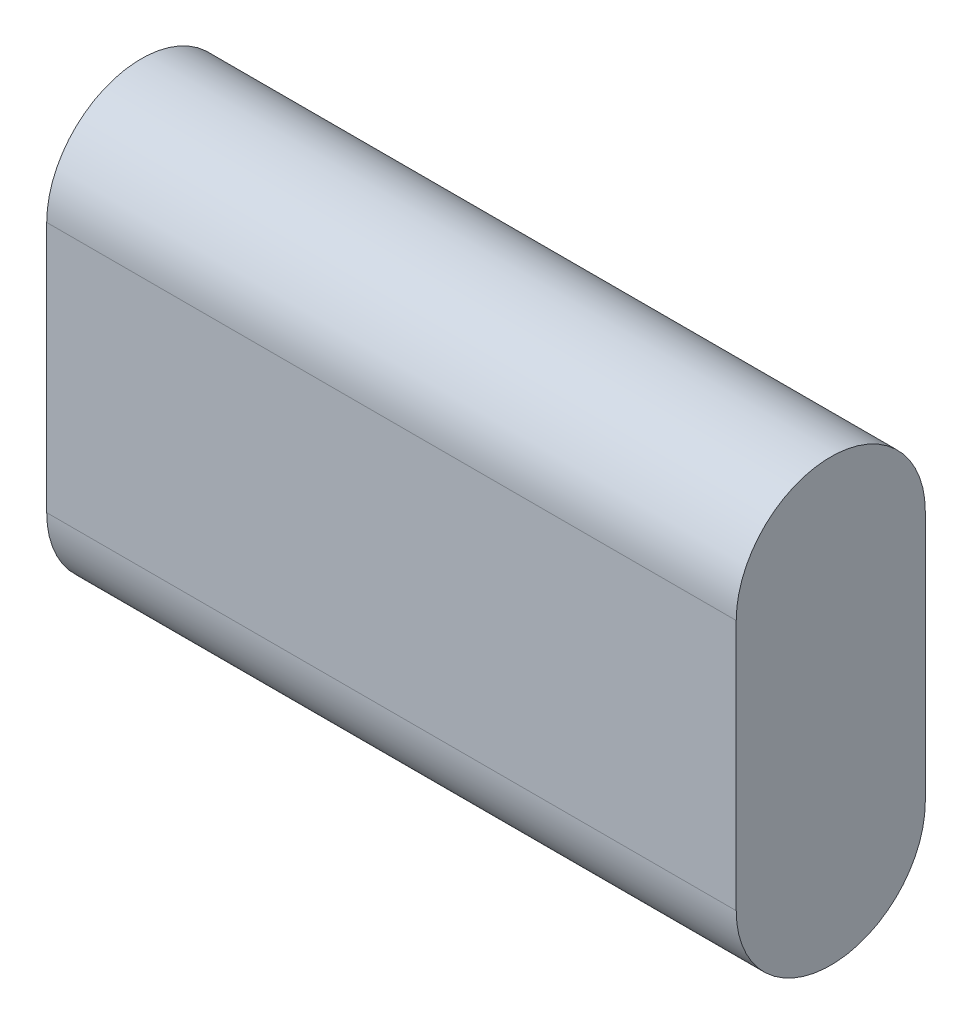
SolidWorks part; units mm, degrees
ref_plane "正面" through (0, 0, 0) normal (0, 0, 1) x (1, 0, 0)
ref_plane "平面" through (0, 0, 0) normal (0, 1, 0) x (1, 0, 0)
ref_plane "右側面" through (0, 0, 0) normal (1, 0, 0) x (0, 0, -1)
sketch "ｽｹｯﾁ1" plane through (0, 0, 0) normal (1, 0, 0) x (0, 0, -1)
  line L0 (0, -5.65) -> (0, 5.65) construction
  line L1 (-4.25, -5.65) -> (-4.25, 5.65)
  line L2 (4.25, -5.65) -> (4.25, 5.65)
  arc A0 (-4.25, -5.65) -> (4.25, -5.65) centre (0, -5.65) ccw
  arc A1 (4.25, 5.65) -> (-4.25, 5.65) centre (0, 5.65) ccw
  point P2 (0, 0)
  dimension "D2" = 19.8
  dimension "D1" = 8.5
extrude "ﾎﾞｽ - 押し出し1" add sketch "ｽｹｯﾁ1" along normal mid plane 31
